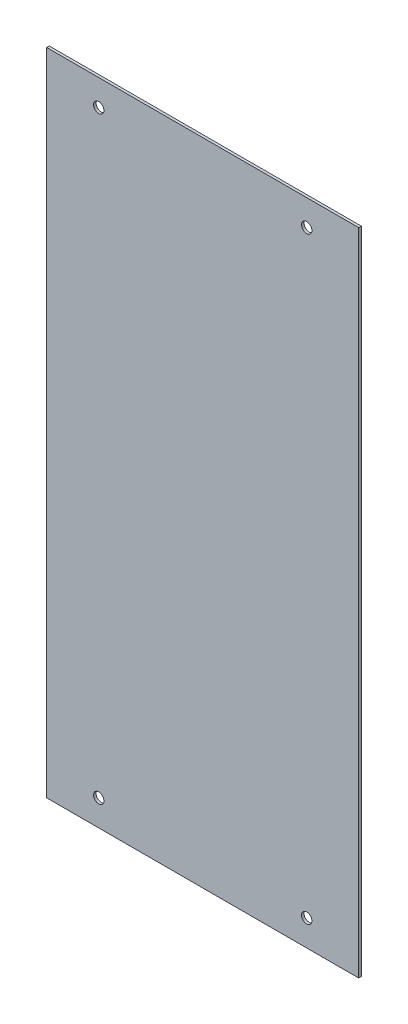
SolidWorks part; units mm, degrees
ref_plane "Plan de face" through (0, 0, 0) normal (0, 0, 1) x (1, 0, 0)
ref_plane "Plan de dessus" through (0, 0, 0) normal (0, 1, 0) x (1, 0, 0)
ref_plane "Plan de droite" through (0, 0, 0) normal (1, 0, 0) x (0, 0, -1)
sketch "Esquisse1" plane through (0, 0, 0) normal (0, 0, 1) x (1, 0, 0)
  line L1 (0, 0) -> (120, 0)
  line L2 (0, 0) -> (0, 250)
  line L3 (0, 250) -> (120, 250)
  line L4 (120, 0) -> (120, 250)
  circle A0 centre (20, 240) radius 2
  circle A1 centre (100, 240) radius 2
  circle A2 centre (100, 10) radius 2
  circle A3 centre (20, 10) radius 2
  dimension "D3" = 4
  dimension "D4" = 4
  dimension "D5" = 4
  dimension "D6" = 4
  dimension "D12" = 20
  dimension "D1" = 120
  dimension "D2" = 250
  dimension "D7" = 10
  dimension "D8" = 10
  dimension "D9" = 10
  dimension "D10" = 10
  dimension "D11" = 20
  dimension "D13" = 20
  dimension "D14" = 20
extrude "Boss.-Extru.1" add sketch "Esquisse1" along normal blind 1
